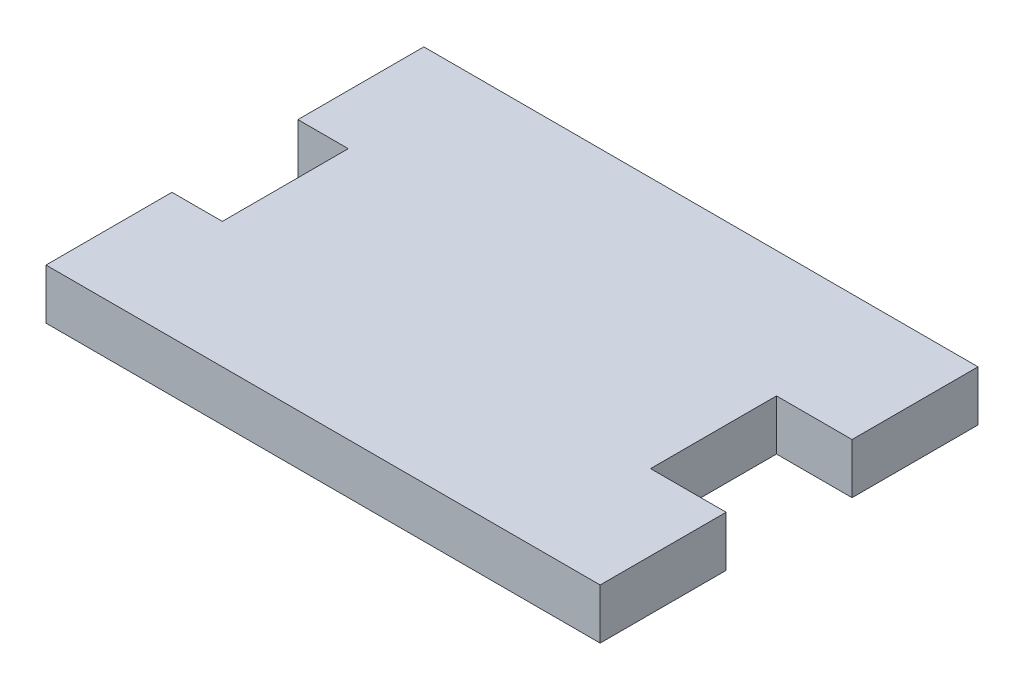
SolidWorks part; units mm, degrees
material "Acrylic (Medium-high impact)"
ref_plane "Front Plane" through (0, 0, 0) normal (0, 0, 1) x (1, 0, 0)
ref_plane "Top Plane" through (0, 0, 0) normal (0, 1, 0) x (1, 0, 0)
ref_plane "Right Plane" through (0, 0, 0) normal (1, 0, 0) x (0, 0, -1)
sketch "Sketch1" plane through (0, 0, 0) normal (0, 1, 0) x (1, 0, 0)
  line L1 (11, -7.5) -> (-11, -7.5)
  line L2 (11, -7.5) -> (11, 7.5)
  line L3 (11, 7.5) -> (-11, 7.5)
  line L4 (-11, -7.5) -> (-11, 7.5)
  line L5 (11, -7.5) -> (-11, 7.5) construction
  line L6 (11, 7.5) -> (-11, -7.5) construction
  point P0 (0, 0)
  dimension "D1" = 22
  dimension "D2" = 15
extrude "Boss-Extrude1" add sketch "Sketch1" along normal blind 2
sketch "Sketch2" plane through (0, 2, 0) normal (0, 1, 0) x (1, 0, 0)
  line L0 (-11, 7.5) -> (-11, -7.5) construction
  line L1 (-9, -2.5) -> (-11, -2.5)
  line L2 (-9, -2.5) -> (-9, 2.5)
  line L3 (-9, 2.5) -> (-11, 2.5)
  line L4 (-11, -2.5) -> (-11, 2.5)
  line L5 (-9, -2.5) -> (-11, 2.5) construction
  line L6 (-9, 2.5) -> (-11, -2.5) construction
  line L7 (11, 7.5) -> (-11, 7.5) construction
  line L8 (11, -7.5) -> (11, 7.5) construction
  line L9 (11, 2.5) -> (8, 2.5)
  line L10 (11, 2.5) -> (11, -2.5)
  line L11 (11, -2.5) -> (8, -2.5)
  line L12 (8, 2.5) -> (8, -2.5)
  point P0 (-10, 0)
  dimension "D1" = 5
  dimension "D2" = 2
  dimension "D3" = 5
  dimension "D4" = 5
  dimension "D5" = 3
  dimension "D6" = 5
extrude "Cut-Extrude1" cut sketch "Sketch2" against normal blind 2
